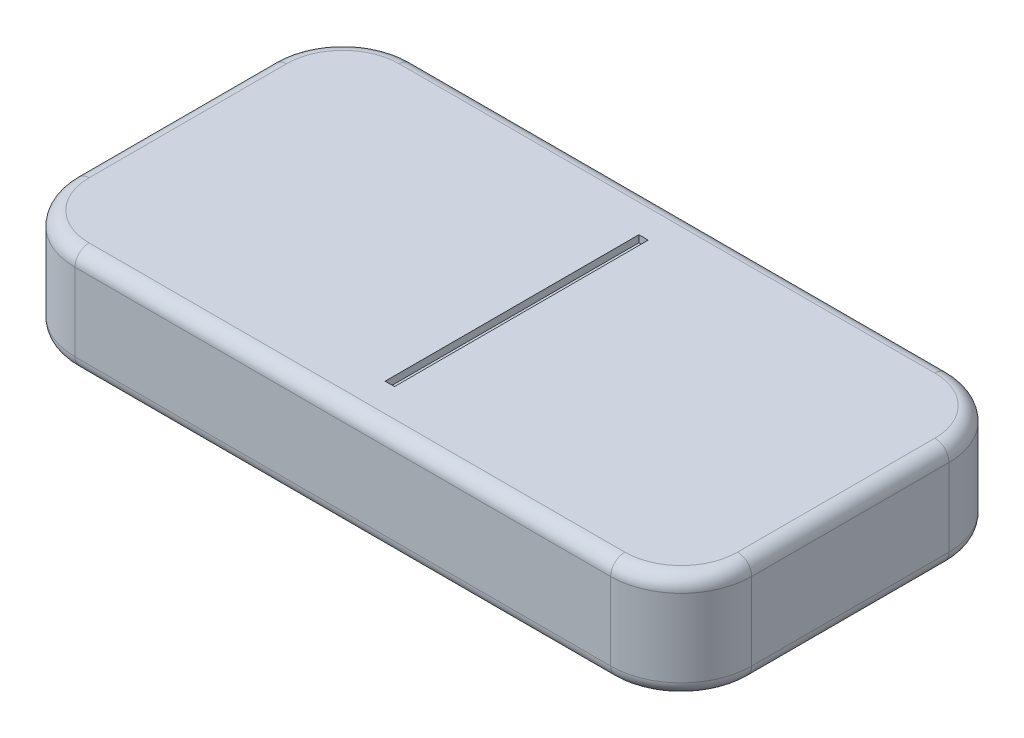
SolidWorks part; units mm, degrees
material "ABS"
ref_plane "Front Plane" through (0, 0, 0) normal (0, 0, 1) x (1, 0, 0)
ref_plane "Top Plane" through (0, 0, 0) normal (0, 1, 0) x (1, 0, 0)
ref_plane "Right Plane" through (0, 0, 0) normal (1, 0, 0) x (0, 0, -1)
sketch "Esquisse1" plane through (0, 0, 0) normal (0, 1, 0) x (1, 0, 0)
  line L1 (0, 0) -> (48, 0)
  line L2 (0, 0) -> (0, 24)
  line L3 (0, 24) -> (48, 24)
  line L4 (48, 0) -> (48, 24)
  dimension "D1" = 48
  dimension "D2" = 24
extrude "Extrusion1" add sketch "Esquisse1" along normal blind 7.5
fillet "Congé2" radius 5 4 edges at (48, 3.75, 0) (48, 3.75, -24) (0, 3.75, 0) (0, 3.75, -24)
fillet "Congé5" radius 1 8 edges at (46.5355, 7.5, -22.5355) (48, 7.5, -12) (46.5355, 7.5, -1.4645) (24, 7.5, 0) (1.4645, 7.5, -1.4645) (0, 7.5, -12) (1.4645, 7.5, -22.5355) (24, 7.5, -24)
fillet "Congé6" radius 1 8 edges at (46.5355, 0, -22.5355) (48, 0, -12) (46.5355, 0, -1.4645) (24, 0, 0) (1.4645, 0, -1.4645) (0, 0, -12) (1.4645, 0, -22.5355) (24, 0, -24)
sketch "Esquisse3" plane through (0, 7.5, 0) normal (0, 1, 0) x (1, 0, 0)
  line L0 (1, 12) -> (24, 12) construction
  line L4 (43, 23) -> (5, 23) construction
  line L6 (5, 1) -> (43, 1) construction
  line L7 (1, 19) -> (1, 5) construction
  line L8 (24, 21) -> (24.6622, 21)
  line L9 (24, 21) -> (24, 3)
  line L10 (24, 3) -> (24.6622, 3)
  line L11 (24.6622, 21) -> (24.6622, 3)
  line L12 (24.6622, 12) -> (47.6622, 12) construction
  dimension "D1" = 2
  dimension "D2" = 2
  dimension "D3" = 23
  dimension "D4" = 23
extrude "Extrusion2" cut sketch "Esquisse3" against normal blind 0.5
